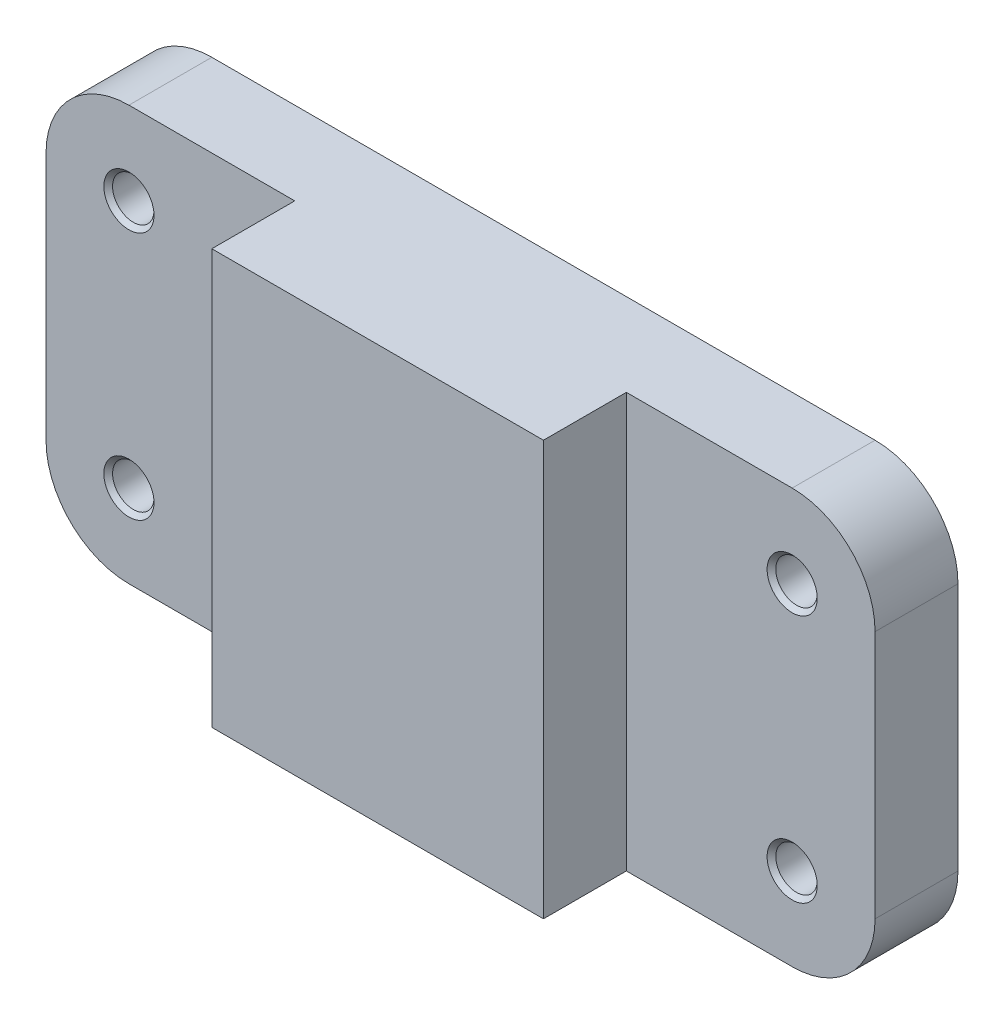
SolidWorks part; units mm, degrees
ref_plane "前视基准面" through (0, 0, 0) normal (0, 0, 1) x (1, 0, 0)
ref_plane "上视基准面" through (0, 0, 0) normal (0, 1, 0) x (1, 0, 0)
ref_plane "右视基准面" through (0, 0, 0) normal (1, 0, 0) x (0, 0, -1)
sketch "草图1" plane through (0, 0, 0) normal (0, 0, 1) x (1, 0, 0)
  line L1 (-50, 25) -> (50, 25)
  line L2 (-50, 25) -> (-50, -25)
  line L3 (-50, -25) -> (50, -25)
  line L4 (50, 25) -> (50, -25)
  line L5 (0, -25) -> (0, 25) construction
  line L6 (-50, 0) -> (50, 0) construction
  point P0 (0, 0)
  dimension "D1" = 100
  dimension "D2" = 50
extrude "凸台-拉伸1" add sketch "草图1" along normal blind 10
sketch "草图2" plane through (0, 0, 10) normal (0, 0, 1) x (1, 0, 0)
  line L0 (-50, -25) -> (50, -25) construction
  line L1 (-20, 25) -> (20, 25)
  line L2 (-20, 25) -> (-20, -25)
  line L3 (-20, -25) -> (20, -25)
  line L4 (20, 25) -> (20, -25)
  line L5 (0, -25) -> (0, 25) construction
  line L6 (-20, 0) -> (20, 0) construction
  point P0 (0, 0)
  dimension "D1" = 40
extrude "凸台-拉伸2" add sketch "草图2" along normal blind 10
fillet "圆角1" radius 10 4 edges at (50, -25, 5) (-50, 25, 5) (50, 25, 5) (-50, -25, 5)
hole_wizard "M6 螺纹孔1" positions "草图3" profile "草图4" tap size "M6" standard "GB" end condition through all
sketch "草图3" plane through (0, 0, 10) normal (0, 0, 1) x (1, 0, 0)
  point P0 (-40, 15)
  point P3 (-40, -15)
  point P6 (40, -15)
  point P9 (40, 15)
sketch "草图4" plane through (-40, 15, 10) normal (1, 0, 0) x (0, -1, 0)
  line L0 (0, 0) -> (0, 10)
  line L1 (0, 10) -> (2.5, 10)
  line L2 (2.5, 10) -> (2.5, 0.525)
  line L3 (2.5, 0.525) -> (3.025, 0)
  line L5 (3.025, 0) -> (0, 0)
  line L6 (-2.5, 0.525) -> (-3.025, 0) construction
  line L11 (0, -6.35) -> (0, 107.95) construction
  dimension "通孔螺纹孔钻头直径" = 5
  dimension "通孔螺纹孔钻头深度" = 10
  dimension "近端锥形沉头孔直径" = 6.05
  dimension "近端锥形沉头孔角度" = 90
cosmetic thread "孔螺蚊线1" parameters "D2"=6
cosmetic thread "孔螺蚊线2" parameters "D2"=6
cosmetic thread "孔螺蚊线3" parameters "D2"=6
cosmetic thread "孔螺蚊线4" parameters "D2"=6
